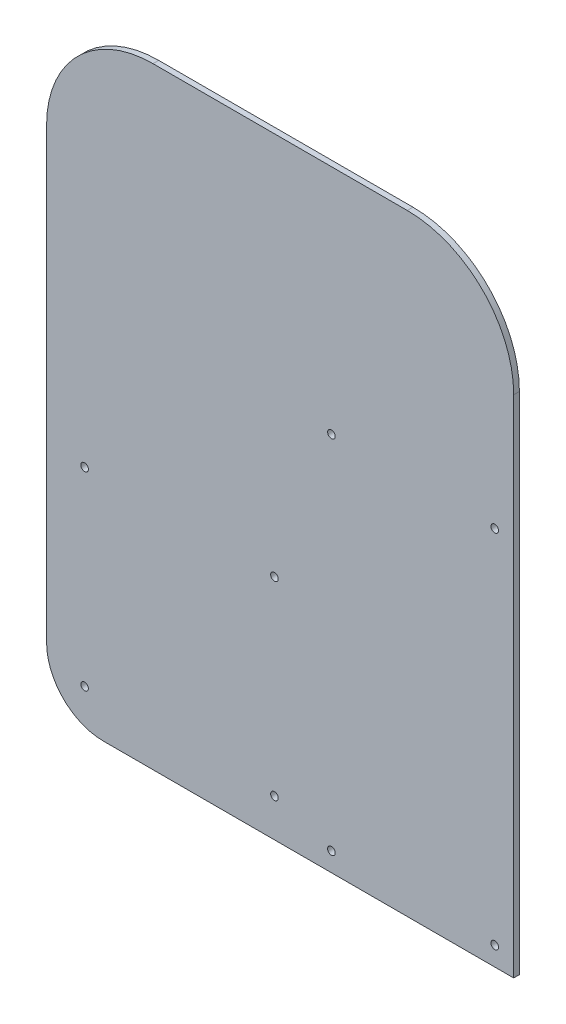
SolidWorks part; units mm, degrees
ref_plane "Alzado" through (0, 0, 0) normal (0, 0, 1) x (1, 0, 0)
ref_plane "Planta" through (0, 0, 0) normal (0, 1, 0) x (1, 0, 0)
ref_plane "Vista lateral" through (0, 0, 0) normal (1, 0, 0) x (0, 0, -1)
sketch "Croquis2" plane through (0, 0, 0) normal (0, 0, 1) x (1, 0, 0)
  line L0 (0, 0) -> (0, 80)
  line L2 (30, -30) -> (110, -30)
  line L4 (70, 292.0369) -> (70, -30) construction
  line L5 (0, 40) -> (140, 40) construction
  line L11 (20, 90) -> (20, -10) construction
  line L24 (20, 90) -> (120, 90) construction
  line L30 (0, 80) -> (0, 235.9889)
  line L31 (246, 180) -> (246, 235.9889)
  line L37 (246, 180) -> (246, -30)
  line L38 (246, -30) -> (140, -30)
  line L40 (140, 292.0369) -> (140, -30) construction
  line L48 (150.0952, 160) -> (150, 160) construction
  line L49 (140, -30) -> (110, -30)
  line L57 (150, 170) -> (152, 170) construction
  line L58 (56.048, 292.0369) -> (189.952, 292.0369)
  arc A1 (0, 0) -> (30, -30) centre (30, 0) ccw
  circle A20 centre (20, -10) radius 2
  circle A21 centre (120, -10) radius 2
  circle A22 centre (120, 90) radius 2
  circle A23 centre (20, 90) radius 2
  circle A24 centre (150, 170) radius 2
  circle A25 centre (236, 170) radius 2
  circle A26 centre (236, -20) radius 2
  circle A27 centre (150, -20) radius 2
  arc A28 (0, 235.9889) -> (56.048, 292.0369) centre (56.048, 235.9889) cw
  arc A29 (246, 235.9889) -> (189.952, 292.0369) centre (189.952, 235.9889) ccw
  point P18 (70, 40)
  point P39 (192.8171, 75.3623)
  point P44 (193, 75)
  dimension "D2" = 4
  dimension "D5" = 4
  dimension "D9" = 4
  dimension "D10" = 100
  dimension "D4" = 4
  dimension "D3" = 70
extrude "Saliente-Extruir2" add sketch "Croquis2" along normal blind 3
